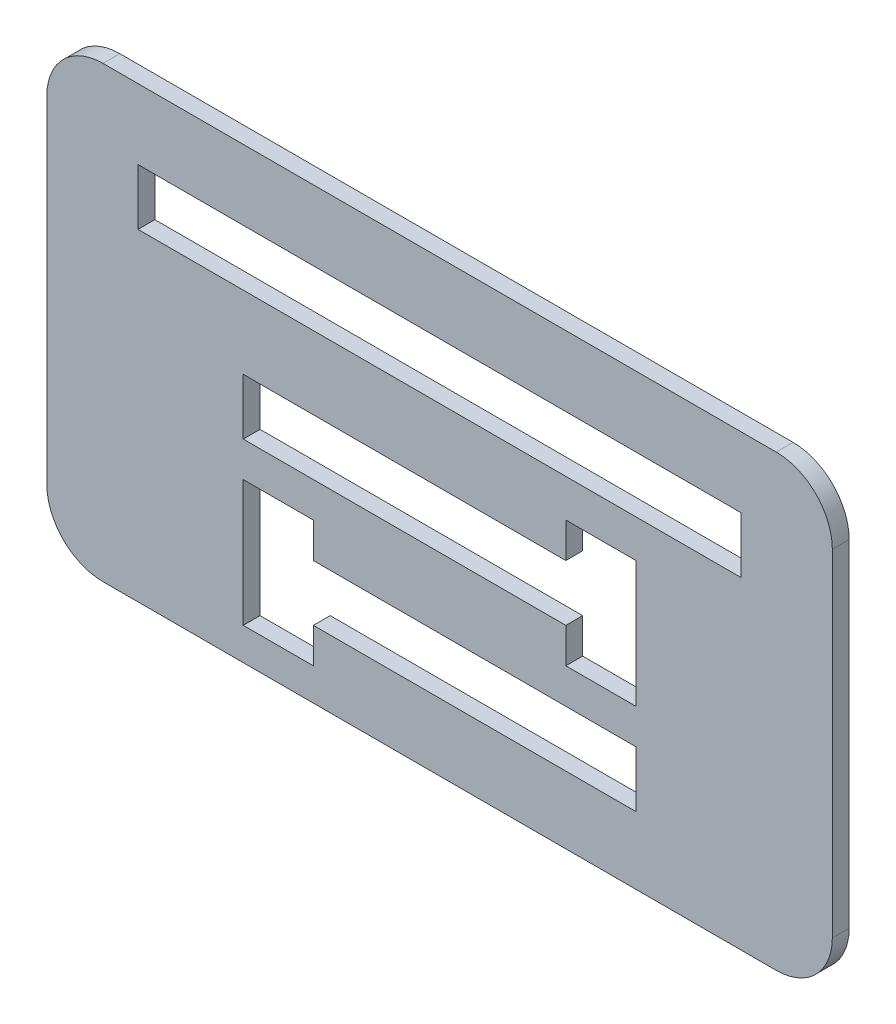
SolidWorks part; units mm, degrees
ref_plane "Front Plane" through (0, 0, 0) normal (0, 0, 1) x (1, 0, 0)
ref_plane "Top Plane" through (0, 0, 0) normal (0, 1, 0) x (1, 0, 0)
ref_plane "Right Plane" through (0, 0, 0) normal (1, 0, 0) x (0, 0, -1)
sketch "Sketch1" plane through (0, 0, 0) normal (0, 0, 1) x (1, 0, 0)
  line L1 (20, 0) -> (260, 0)
  line L2 (0, 20) -> (0, 140)
  line L3 (20, 160) -> (260, 160)
  line L4 (280, 20) -> (280, 140)
  arc A0 (260, 0) -> (280, 20) centre (260, 20) ccw
  arc A1 (260, 160) -> (280, 140) centre (260, 140) cw
  arc A2 (0, 140) -> (20, 160) centre (20, 140) cw
  arc A3 (20, 0) -> (0, 20) centre (20, 20) cw
  point P7 (280, 0)
  point P10 (280, 160)
  point P13 (0, 160)
  point P16 (0, 0)
  dimension "D3" = 20
  dimension "D1" = 280
  dimension "D2" = 160
extrude "Boss-Extrude1" add sketch "Sketch1" along normal blind 6
sketch "Sketch2" plane through (0, 0, 6) normal (0, 0, 1) x (1, 0, 0)
  line L0 (15, 137.5) -> (15, 160) construction
  line L1 (32.5, 115) -> (0, 115) construction
  line L2 (32.5, 135) -> (247.5, 135)
  line L3 (32.5, 135) -> (32.5, 115)
  line L4 (32.5, 115) -> (247.5, 115)
  line L6 (15, 22.5) -> (15, 0) construction
  line L7 (247.5, 135) -> (247.5, 115)
  line L8 (70, 89.0139) -> (185, 89.0139)
  line L9 (70, 89.0139) -> (70, 69.0139)
  line L10 (70, 69.0139) -> (185, 69.0139)
  line L11 (185, 69.0139) -> (185, 56.5139)
  line L12 (185, 101.5139) -> (210, 101.5139)
  line L13 (185, 101.5139) -> (185, 89.0139)
  line L14 (185, 56.5139) -> (210, 56.5139)
  line L15 (210, 101.5139) -> (210, 56.5139)
  line L16 (70, 69.0139) -> (0, 69.0139) construction
  line L17 (210, 69.0139) -> (280, 69.0139) construction
  line L24 (0, 140) -> (0, 20) construction
  line L25 (247.5, 115) -> (280, 115) construction
  line L26 (280, 20) -> (280, 140) construction
  line L27 (260, 160) -> (20, 160) construction
  line L30 (95, 56.5139) -> (95, 44.0139)
  line L31 (210, 44.0139) -> (95, 44.0139)
  line L32 (70, 56.5139) -> (70, 11.5139)
  line L33 (210, 24.0139) -> (95, 24.0139)
  line L34 (210, 44.0139) -> (210, 24.0139)
  line L35 (95, 11.5139) -> (70, 11.5139)
  line L36 (95, 56.5139) -> (70, 56.5139)
  line L37 (95, 24.0139) -> (95, 11.5139)
  dimension "D3" = 25
  dimension "D1" = 215
  dimension "D2" = 20
  dimension "D4" = 45
  dimension "D6" = 25
  dimension "D7" = 115
  dimension "D5" = 20
extrude "Cut-Extrude1" cut sketch "Sketch2" against normal blind 6
